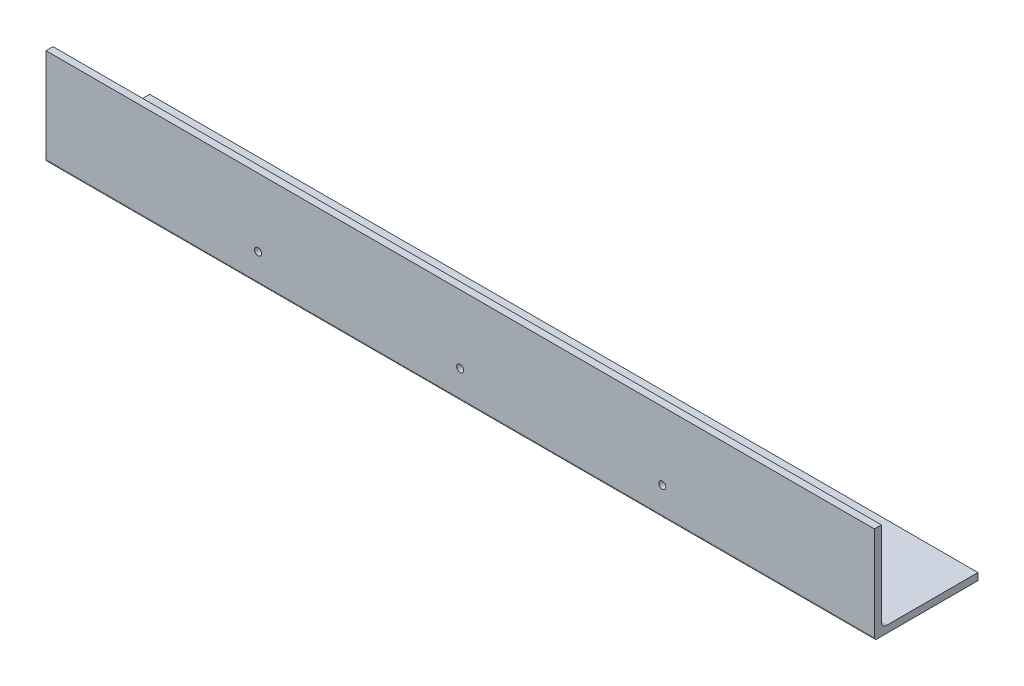
SolidWorks part; units mm, degrees
ref_plane "Alzado" through (0, 0, 0) normal (0, 0, 1) x (1, 0, 0)
ref_plane "Planta" through (0, 0, 0) normal (0, 1, 0) x (1, 0, 0)
ref_plane "Vista lateral" through (0, 0, 0) normal (1, 0, 0) x (0, 0, -1)
sketch "Croquis1" plane through (0, 0, 0) normal (0, 0, 1) x (1, 0, 0)
  line L0 (235.625, 27.5) -> (-235.625, -27.5) construction
  line L1 (-235.625, 27.5) -> (235.625, 27.5)
  line L2 (-235.625, 27.5) -> (-235.625, -27.5)
  line L3 (-235.625, -27.5) -> (235.625, -27.5)
  line L4 (235.625, 27.5) -> (235.625, -27.5)
  dimension "D1" = 471.25
  dimension "D2" = 55
extrude "Saliente-Extruir1" add sketch "Croquis1" along normal blind 4
sketch "Croquis2" plane through (0, 0, 0) normal (0, 0, -1) x (-1, 0, 0)
  line L0 (-235.625, -27.5) -> (-235.625, 27.5) construction
  line L1 (-235.625, -23.5) -> (235.625, -23.5)
  line L2 (-235.625, -23.5) -> (-235.625, -27.5)
  line L3 (-235.625, -27.5) -> (235.625, -27.5)
  line L4 (235.625, -23.5) -> (235.625, -27.5)
  dimension "D1" = 4
extrude "Saliente-Extruir2" add sketch "Croquis2" along normal blind 55
fillet "Redondeo1" radius 3 1 edges
fillet "Redondeo2" radius 1.5 1 edges at (0, -27.5, 4)
sketch "Croquis3" plane through (0, 0, 4) normal (0, 0, 1) x (1, 0, 0)
  circle A0 centre (-115, -11.2375) radius 2
  circle A1 centre (0, -11.2375) radius 2
  circle A2 centre (115, -11.2375) radius 2
extrude "Cortar-Extruir1" cut sketch "Croquis3" against normal up to next
